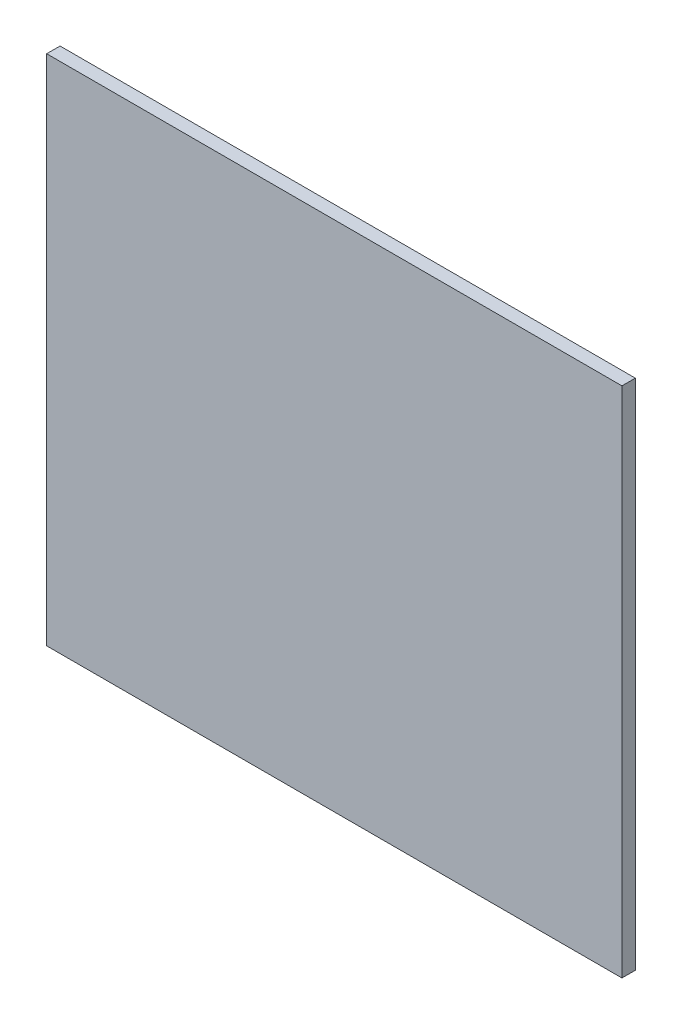
SolidWorks part; units mm, degrees
ref_plane "Plano frontal" through (0, 0, 0) normal (0, 0, 1) x (1, 0, 0)
ref_plane "Plano superior" through (0, 0, 0) normal (0, 1, 0) x (1, 0, 0)
ref_plane "Plano direito" through (0, 0, 0) normal (1, 0, 0) x (0, 0, -1)
sketch "Esboço1" plane through (0, 0, 0) normal (0, 0, 1) x (1, 0, 0)
  line L0 (0, 0) -> (0, 230)
  line L1 (0, 230) -> (-258, 230)
  line L2 (-258, 230) -> (-258, 0)
  line L3 (-258, 0) -> (0, 0)
  dimension "D1" = 230
  dimension "D2" = 258
extrude "Ressalto-extrusão1" add sketch "Esboço1" along normal blind 6
